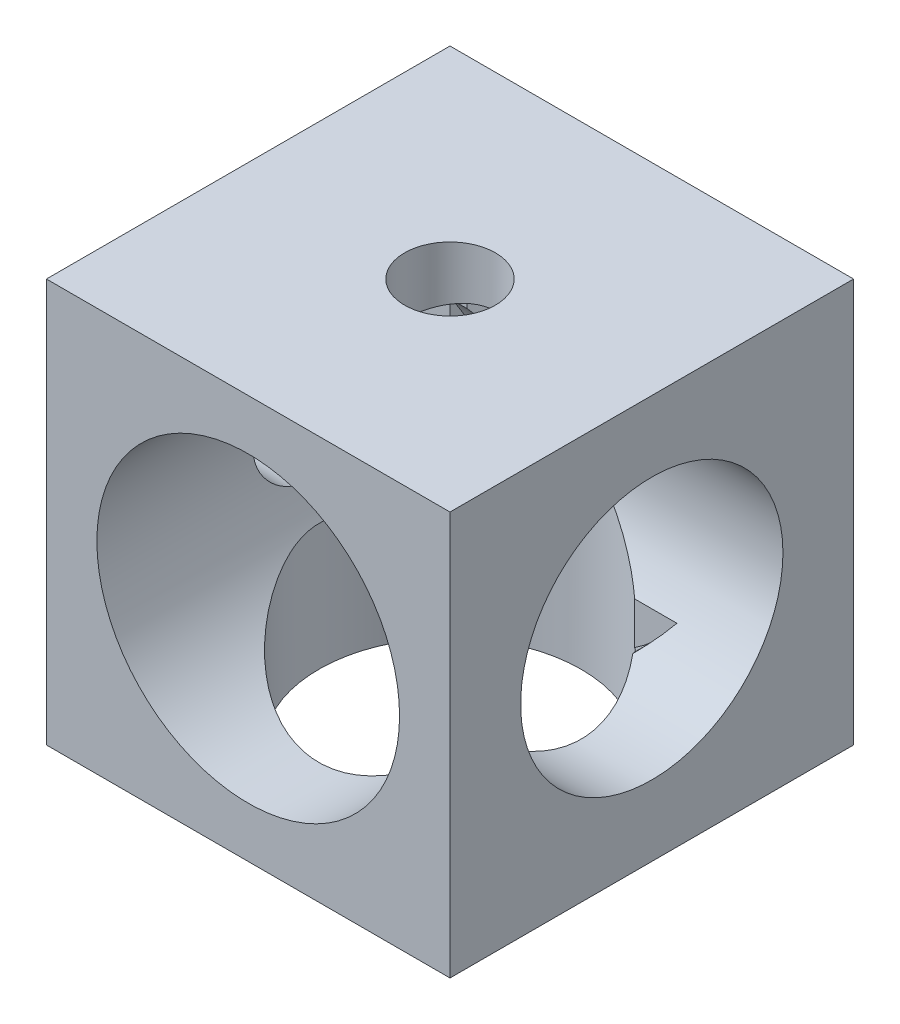
SolidWorks part; units mm, degrees
material "6061 合金"
ref_plane "前视基准面" through (0, 0, 0) normal (0, 0, 1) x (1, 0, 0)
ref_plane "上视基准面" through (0, 0, 0) normal (0, 1, 0) x (1, 0, 0)
ref_plane "右视基准面" through (0, 0, 0) normal (1, 0, 0) x (0, 0, -1)
other "Configuration Table"
sketch "草图1" plane through (0, 0, 0) normal (0, 1, 0) x (1, 0, 0)
  line L1 (10, -10) -> (-10, -10)
  line L2 (10, -10) -> (10, 10)
  line L3 (10, 10) -> (-10, 10)
  line L4 (-10, -10) -> (-10, 10)
  line L5 (10, -10) -> (-10, 10) construction
  line L6 (10, 10) -> (-10, -10) construction
  point P0 (0, 0)
  dimension "D1" = 20
extrude "凸台-拉伸1" add sketch "草图1" along normal blind 20
sketch "草图2" plane through (0, 0, 0) normal (0, -1, 0) x (1, 0, 0)
  circle A0 centre (0, 0) radius 6.5
  dimension "D1" = 13
extrude "切除-拉伸1" cut sketch "草图2" against normal blind 15
sketch "草图3" plane through (10, 0, 0) normal (1, 0, 0) x (0, 0, -1)
  line L0 (10, 20) -> (10, 0) construction
  circle A0 centre (0, 10) radius 6.5
  point P4 (10, 10)
  dimension "D1" = 13
extrude "切除-拉伸2" cut sketch "草图3" against normal blind 15
sketch "草图4" plane through (0, 0, 10) normal (0, 0, 1) x (1, 0, 0)
  line L0 (10, 20) -> (10, 0) construction
  circle A0 centre (0, 10) radius 7.5
  point P4 (10, 10)
  dimension "D1" = 15
extrude "切除-拉伸3" cut sketch "草图4" against normal blind 15
sketch "草图5" plane through (0, 0, 0) normal (0, -1, 0) x (1, 0, 0)
  circle A0 centre (0, 0) radius 2.25
  dimension "D1" = 4.5
extrude "切除-拉伸5" cut sketch "草图5" against normal through all both and the other way through all
sketch "草图6" plane through (0, 0, 10) normal (0, 0, 1) x (1, 0, 0)
  circle A0 centre (0, 10) radius 2.25
  dimension "D1" = 4.5
extrude "切除-拉伸6" cut sketch "草图6" against normal through all both and the other way through all
sketch "草图7" plane through (10, 0, 0) normal (1, 0, 0) x (0, 0, -1)
  circle A0 centre (0, 10) radius 2.25
  dimension "D1" = 4.5
extrude "切除-拉伸7" cut sketch "草图7" against normal through all both and the other way through all
